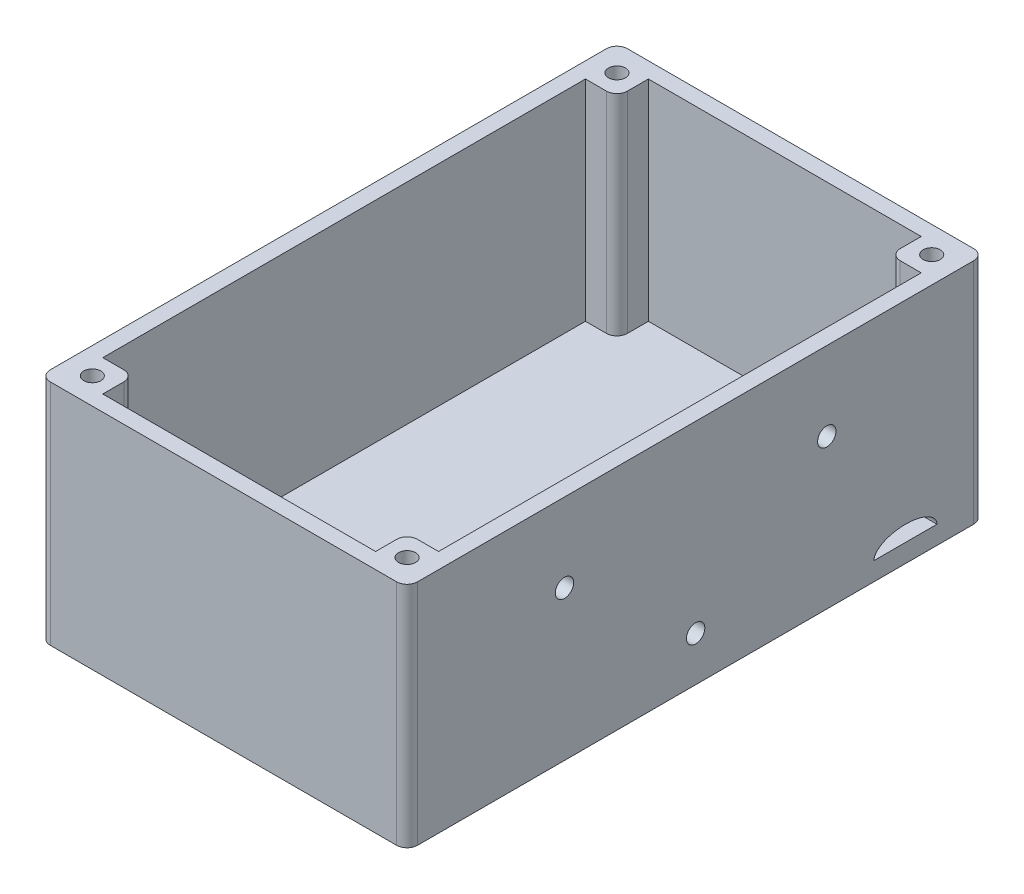
SolidWorks part; units mm, degrees
ref_plane "Front Plane" through (0, 0, 0) normal (0, 0, 1) x (1, 0, 0)
ref_plane "Top Plane" through (0, 0, 0) normal (0, 1, 0) x (1, 0, 0)
ref_plane "Right Plane" through (0, 0, 0) normal (1, 0, 0) x (0, 0, -1)
sketch "Sketch1" plane through (0, 0, 0) normal (0, 1, 0) x (1, 0, 0)
  line L1 (35, -55) -> (-35, -55)
  line L2 (35, -55) -> (35, 55)
  line L3 (35, 55) -> (-35, 55)
  line L4 (-35, -55) -> (-35, 55)
  line L5 (35, -55) -> (-35, 55) construction
  line L6 (35, 55) -> (-35, -55) construction
  point P0 (0, 0)
  dimension "D1" = 110
  dimension "D2" = 70
extrude "Bottom" add sketch "Sketch1" along normal blind 3.5
sketch "Sketch3" plane through (0, 3.5, 0) normal (0, 1, 0) x (1, 0, 0)
  line L0 (-35, 55) -> (35, 55)
  line L1 (35, 55) -> (35, -55)
  line L2 (35, -55) -> (-35, -55)
  line L3 (-35, -55) -> (-35, 55)
  line L4 (-26, 52) -> (-4, 52)
  line L5 (32, 46) -> (32, -46)
  line L6 (26, -52) -> (4, -52)
  line L8 (-32, 46) -> (-26, 46)
  line L9 (-26, 46) -> (-26, 52)
  line L10 (26, 52) -> (26, 46)
  line L11 (26, 46) -> (32, 46)
  line L12 (32, -46) -> (26, -46)
  line L13 (26, -46) -> (26, -52)
  line L14 (-32, -46) -> (-26, -46)
  line L15 (-26, -46) -> (-26, -52)
  line L16 (-32, -46) -> (-32, 46)
  line L23 (-4, 52) -> (26, 52)
  line L26 (4, -52) -> (-26, -52)
  dimension "D1" = 3
  dimension "D2" = 3
  dimension "D3" = 3
  dimension "D4" = 3
  dimension "D5" = 6
extrude "Wall" add sketch "Sketch3" along normal blind 40
sketch "Sketch4" plane through (0, 43.5, 0) normal (0, 1, 0) x (1, 0, 0)
  line L0 (-35, 55) -> (-35, -55) construction
  line L1 (35, 55) -> (-35, 55) construction
  line L2 (35, -55) -> (35, 55) construction
  line L3 (-35, -55) -> (35, -55) construction
  line L5 (35, 0) -> (33.8613, 0) construction
  circle A0 centre (-30, 50) radius 1.625
  circle A1 centre (30, 50) radius 1.625
  circle A2 centre (30, -50) radius 1.625
  circle A3 centre (-30, -50) radius 1.625
  dimension "D1" = 3.25
  dimension "D4" = 5
  dimension "D2" = 5
  dimension "D3" = 5
  dimension "D5" = 5
extrude "Top Plate Screw Holes" cut sketch "Sketch4" against normal blind 30 draft 1
fillet "Fillet1" radius 2 1 edges at (-26, 23.5, 46)
fillet "Fillet2" radius 2 1 edges at (26, 23.5, 46)
fillet "Fillet3" radius 2 1 edges at (26, 23.5, -46)
fillet "Fillet4" radius 2 1 edges at (-26, 23.5, -46)
fillet "Fillet5" radius 2 1 edges at (-35, 21.75, -55)
fillet "Fillet6" radius 2 1 edges at (35, 21.75, -55)
fillet "Fillet7" radius 2 1 edges at (35, 21.75, 55)
fillet "Fillet8" radius 2 1 edges at (-35, 21.75, 55)
sketch "M4 Mount" plane through (0, 3.5, 0) normal (0, -1, 0) x (1, 0, 0)
  line L1 (0, 0) -> (23.8675, 0) construction
  line L2 (0, 0) -> (0, -20) construction
  circle A0 centre (0, -20) radius 2.1
  circle A1 centre (0, 20) radius 2.1
  dimension "D1" = 4.2
  dimension "D3" = 20
  dimension "D4" = 20
extrude "M4 Mount Cut" cut sketch "M4 Mount" along normal through all
sketch "M4 Screw Heads" plane through (0, 3.5, 0) normal (0, 1, 0) x (1, 0, 0)
  circle A0 centre (0, -20) radius 3.75
  circle A1 centre (0, 20) radius 3.75
  dimension "D1" = 7.5
extrude "M4 Screw CUT" cut sketch "M4 Screw Heads" against normal blind 10 draft 45
sketch "Sketch5" plane through (32, 0, 0) normal (-1, 0, 0) x (0, 0, 1)
  line L1 (-46, 3.5) -> (-34, 3.5)
  line L2 (46, 3.5) -> (-46, 3.5) construction
  ellipse E0 centre (-40, 3.5) end of major axis (-34, 3.5) minor radius 3 (-34, 3.5) -> (-46, 3.5) ccw
  dimension "D1" = 3
  dimension "D2" = 12
extrude "Cable Pass CUT" cut sketch "Sketch5" against normal blind 10
sketch "Sketch6" plane through (32, 0, 0) normal (-1, 0, 0) x (0, 0, 1)
  line L0 (0, 43.5) -> (0, 18.1138) construction
  line L1 (46, 43.5) -> (-46, 43.5) construction
  line L2 (-46, 23.5) -> (-28.6375, 23.5) construction
  line L3 (-46, 43.5) -> (-46, 3.5) construction
  circle A0 centre (-25, 28.5) radius 1.75
  circle A1 centre (25, 28.5) radius 1.75
  circle A2 centre (0, 8.5) radius 1.75
  dimension "D1" = 3.5
  dimension "D3" = 15
  dimension "D2" = 25
  dimension "D4" = 5
extrude "M3 Connection CUT" cut sketch "Sketch6" against normal blind 10
equation "\"BOXWALL\"=3"
equation "\"D1@Sketch3\"=\"BOXWALL\""
equation "\"D2@Sketch3\"=\"BOXWALL\""
equation "\"D3@Sketch3\"=\"BOXWALL\""
equation "\"D4@Sketch3\"=\"BOXWALL\""
equation "\"SCREW_M3\"=3.5"
equation "\"D1@Sketch6\"=\"SCREW_M3\""
